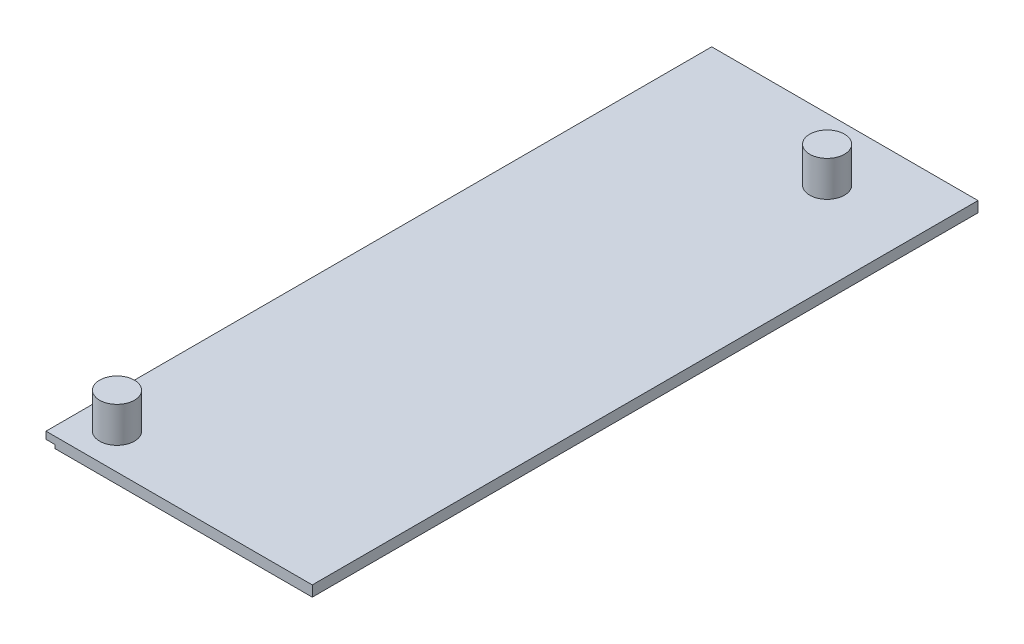
SolidWorks part; units mm, degrees
ref_plane "Front Plane" through (0, 0, 0) normal (0, 0, 1) x (1, 0, 0)
ref_plane "Top Plane" through (0, 0, 0) normal (0, 1, 0) x (1, 0, 0)
ref_plane "Right Plane" through (0, 0, 0) normal (1, 0, 0) x (0, 0, -1)
sketch "Sketch1" plane through (0, 0, 0) normal (0, 0, 1) x (1, 0, 0)
  line L1 (0, 0) -> (75, 0)
  line L2 (0, 0) -> (0, 3)
  line L3 (0, 3) -> (75, 3)
  line L4 (75, 0) -> (75, 3)
  dimension "D1" = 3
  dimension "D2" = 75
extrude "Boss-Extrude1" add sketch "Sketch1" along normal blind 187.5
sketch "Sketch2" plane through (0, 3, 0) normal (0, 1, 0) x (1, 0, 0)
  line L0 (75, -187.5) -> (75, 0) construction
  line L1 (112.5, 12.5) -> (-112.5, 12.5)
  line L2 (112.5, 12.5) -> (112.5, -187.5)
  line L3 (112.5, -187.5) -> (-112.5, -187.5)
  line L4 (-112.5, 12.5) -> (-112.5, -187.5)
  line L5 (100, -187.5) -> (-100, -187.5)
  line L6 (100, -187.5) -> (100, 12.5)
  line L7 (100, 12.5) -> (-100, 12.5)
  line L8 (-100, -187.5) -> (-100, 12.5)
  line L9 (75, -187.5) -> (0, -187.5) construction
  circle A0 centre (90, -177.5) radius 4.9
  circle A1 centre (50, -17.5) radius 4.9
  circle A2 centre (10, -177.5) radius 4.9
  dimension "D4" = 10
  dimension "D5" = 10
  dimension "D6" = 9.8
  dimension "D7" = 9.8
  dimension "D8" = 30
  dimension "D9" = 40
  dimension "D11" = 10
  dimension "D12" = 40
  dimension "D13" = 9.8
  dimension "D1" = 225
  dimension "D2" = 12.5
  dimension "D3" = 12.5
  dimension "D10" = 25
extrude "Boss-Extrude2" add sketch "Sketch2" along normal blind 10 contours A1 | A2
sketch "Sketch3" plane through (0, 0, 0) normal (0, -1, 0) x (1, 0, 0)
  line L1 (4, 43) -> (11, 43)
  line L2 (4, 43) -> (4, 10)
  line L3 (4, 10) -> (11, 10)
  line L4 (11, 43) -> (11, 10)
  line L5 (4, 47) -> (11, 47)
  line L6 (4, 47) -> (4, 80)
  line L7 (4, 80) -> (11, 80)
  line L8 (11, 47) -> (11, 80)
  line L44 (0, 187.5) -> (0, 0) construction
  line L45 (19, 43) -> (26, 43)
  line L46 (19, 43) -> (19, 10)
  line L47 (19, 10) -> (26, 10)
  line L48 (26, 43) -> (26, 10)
  line L49 (19, 47) -> (26, 47)
  line L50 (19, 47) -> (19, 80)
  line L51 (19, 80) -> (26, 80)
  line L52 (26, 47) -> (26, 80)
  line L53 (34, 43) -> (41, 43)
  line L54 (34, 43) -> (34, 10)
  line L55 (34, 10) -> (41, 10)
  line L56 (41, 43) -> (41, 10)
  line L57 (34, 47) -> (41, 47)
  line L58 (34, 47) -> (34, 80)
  line L59 (34, 80) -> (41, 80)
  line L60 (41, 47) -> (41, 80)
  line L61 (49, 43) -> (56, 43)
  line L62 (49, 43) -> (49, 10)
  line L63 (49, 10) -> (56, 10)
  line L64 (56, 43) -> (56, 10)
  line L65 (49, 47) -> (56, 47)
  line L66 (49, 47) -> (49, 80)
  line L67 (49, 80) -> (56, 80)
  line L68 (56, 47) -> (56, 80)
  line L69 (64, 43) -> (71, 43)
  line L70 (64, 43) -> (64, 10)
  line L71 (64, 10) -> (71, 10)
  line L72 (71, 43) -> (71, 10)
  line L73 (64, 47) -> (71, 47)
  line L74 (64, 47) -> (64, 80)
  line L75 (64, 80) -> (71, 80)
  line L76 (71, 47) -> (71, 80)
  line L78 (0, 0) -> (75, 0) construction
  line L88 (0, 187.5) -> (2.5, 187.5)
  line L89 (0, 187.5) -> (0, 85)
  line L90 (0, 85) -> (2.5, 85)
  line L91 (2.5, 187.5) -> (2.5, 85)
  dimension "D1" = 70
  dimension "D2" = 33
  dimension "D3" = 33
  dimension "D4" = 7
  dimension "D5" = 7
  dimension "D7" = 4
  dimension "D6" = 4
  dimension "D9" = 10
  dimension "D10" = 2.5
  dimension "D11" = 5
  dimension "D8" = 5
extrude "Cut-Extrude1" cut sketch "Sketch3" against normal blind 1
